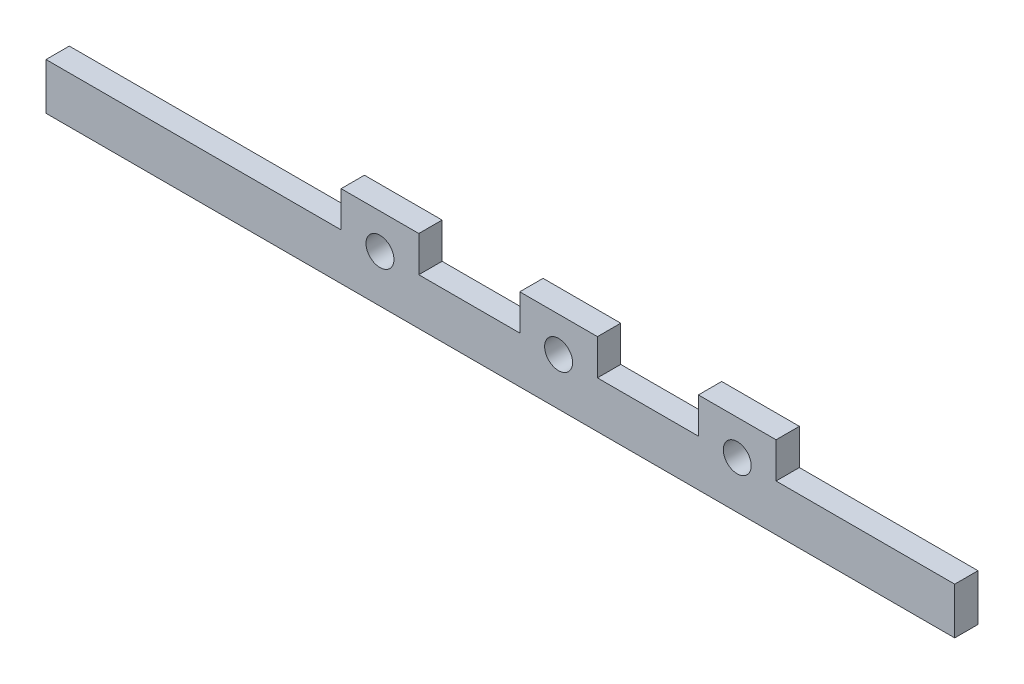
SolidWorks part; units mm, degrees
ref_plane "Alzado" through (0, 0, 0) normal (0, 0, 1) x (1, 0, 0)
ref_plane "Planta" through (0, 0, 0) normal (0, 1, 0) x (1, 0, 0)
ref_plane "Vista lateral" through (0, 0, 0) normal (1, 0, 0) x (0, 0, -1)
sketch "Croquis1" plane through (0, 0, 0) normal (0, 0, 1) x (1, 0, 0)
  line L0 (-292.5, 0) -> (292.5, 0)
  line L1 (-102.5, 30) -> (-292.5, 30)
  line L2 (12.5, 30) -> (12.5, 53)
  line L3 (12.5, 53) -> (62.5, 53)
  line L4 (62.5, 30) -> (62.5, 53)
  line L5 (177.5, 30) -> (292.5, 30)
  line L6 (-102.5, 30) -> (-102.5, 53)
  line L7 (-102.5, 53) -> (-52.5, 53)
  line L8 (-52.5, 30) -> (-52.5, 53)
  line L9 (12.5, 30) -> (-52.5, 30)
  line L10 (-292.5, 0) -> (-292.5, 30)
  line L11 (-77.5, 30.5) -> (-102.5, 30.5) construction
  line L12 (127.5, 30) -> (127.5, 53)
  line L13 (62.5, 30) -> (127.5, 30)
  line L14 (292.5, 0) -> (292.5, 30)
  line L15 (127.5, 53) -> (177.5, 53)
  line L16 (177.5, 30) -> (177.5, 53)
  line L17 (37.5, 0) -> (37.5, 53) construction
  line L18 (37.5, 30.5) -> (12.5, 30.5) construction
  line L19 (152.5, 30.5) -> (127.5, 30.5) construction
  circle A0 centre (37.5, 30.5) radius 9
  circle A1 centre (-77.5, 30.5) radius 9
  circle A2 centre (152.5, 30.5) radius 9
  point P0 (0, 0)
  dimension "D3" = 30.5
  dimension "D8" = 18
  dimension "D1" = 585
  dimension "D2" = 330
  dimension "D4" = 65
  dimension "D5" = 30
  dimension "D7" = 53
  dimension "D9" = 50
  dimension "D10" = 65
extrude "Saliente-Extruir1" add sketch "Croquis1" along normal blind 15
